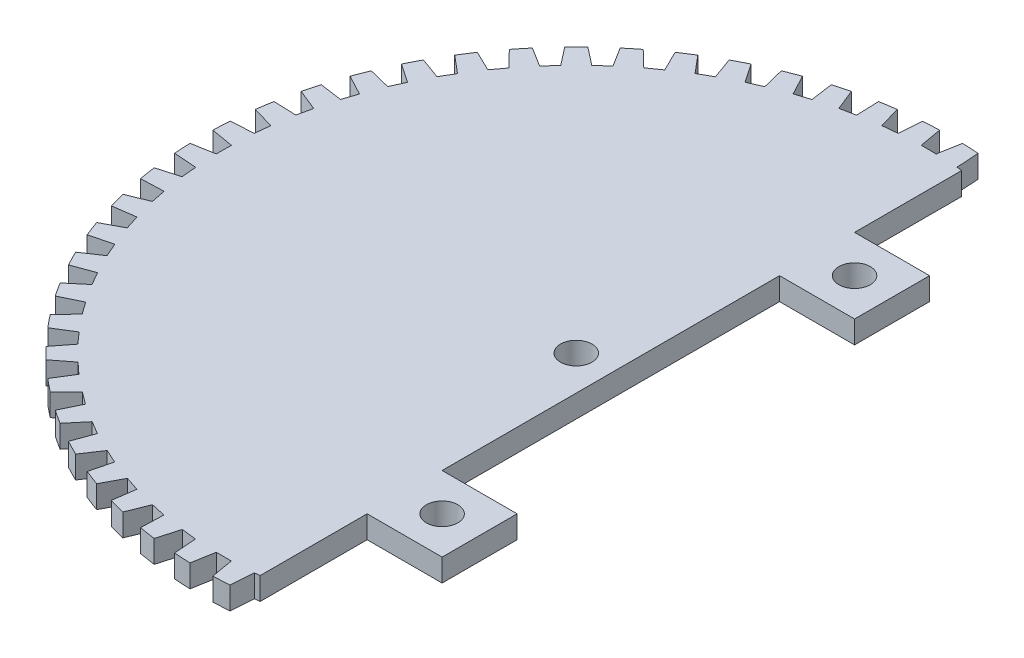
SolidWorks part; units mm, degrees
ref_plane "Спереди" through (0, 0, 0) normal (0, 0, 1) x (1, 0, 0)
ref_plane "Сверху" through (0, 0, 0) normal (0, 1, 0) x (1, 0, 0)
ref_plane "Справа" through (0, 0, 0) normal (1, 0, 0) x (0, 0, -1)
sketch "Эскиз1" plane through (0, 0, 0) normal (0, 1, 0) x (1, 0, 0)
  circle A0 centre (0, 0) radius 50
  dimension "D1" = 100
extrude "Бобышка-Вытянуть1" add sketch "Эскиз1" along normal blind 3
sketch "Эскиз2" plane through (0, 3, 0) normal (0, 1, 0) x (1, 0, 0)
  line L0 (0, 50) -> (0, 47)
  line L1 (-1, 47.0106) -> (1, 46.9894)
  line L2 (1, 46.9894) -> (1.5267, 49.9767)
  line L4 (-1, 47.0106) -> (-1.523, 49.9768)
  circle A0 centre (0, 0) radius 50 construction
  arc A1 (1, 46.9894) -> (0, 47) centre (0, 0) ccw
  arc A3 (1.5267, 49.9767) -> (-1.523, 49.9768) centre (0, 0) ccw
  point P11 (0, 47)
  dimension "D4" = 10
  dimension "D1" = 3
  dimension "D2" = 2
  dimension "D3" = 10
extrude "Вырез-Вытянуть1" cut sketch "Эскиз2" against normal blind 3 contours L1 L4 A3 L2
pattern_circular "Круговой массив1" count 60 over 360 about axis through (0, 0, 0) along (0, 1, 0) of "Вырез-Вытянуть1"
sketch "Эскиз3" plane through (0, 3, 0) normal (0, 1, 0) x (1, 0, 0)
  circle A0 centre (0, 0) radius 2.1
  dimension "D1" = 4.2
extrude "Вырез-Вытянуть2" cut sketch "Эскиз3" against normal blind 3
sketch "Эскиз6" plane through (0, 3, 0) normal (0, 1, 0) x (1, 0, 0)
  line L0 (4.6115, -19.6891) -> (4.6115, 19.6891) construction
  point P3 (4.6115, 0)
ref_plane "Плоскость1" through (4.6115, 0, 0) normal (1, 0, 0) x (0, 0, -1)
sketch "Эскиз7" plane through (4.6115, 0, 0) normal (1, 0, 0) x (0, 0, -1)
  line L1 (-53.0319, 13.837) -> (54.7228, 13.837)
  line L2 (-53.0319, 13.837) -> (-53.0319, -11.6798)
  line L3 (-53.0319, -11.6798) -> (54.7228, -11.6798)
  line L4 (54.7228, 13.837) -> (54.7228, -11.6798)
extrude "Вырез-Вытянуть3" cut sketch "Эскиз7" along normal blind 63
sketch "Эскиз8" plane through (0, 3, 0) normal (0, 1, 0) x (1, 0, 0)
  line L0 (4.6115, -46.771) -> (4.6115, 46.7774) construction
  line L1 (-5.3885, 32.5) -> (14.6115, 32.5)
  line L2 (-5.3885, 32.5) -> (-5.3885, 22.5)
  line L3 (-5.3885, 22.5) -> (14.6115, 22.5)
  line L4 (14.6115, 32.5) -> (14.6115, 22.5)
  line L5 (-5.3885, 32.5) -> (14.6115, 22.5) construction
  line L6 (-5.3885, 22.5) -> (14.6115, 32.5) construction
  line L8 (-5.3885, -22.5) -> (14.6115, -22.5)
  line L9 (-5.3885, -22.5) -> (-5.3885, -32.5)
  line L10 (-5.3885, -32.5) -> (14.6115, -32.5)
  line L11 (14.6115, -22.5) -> (14.6115, -32.5)
  line L12 (-5.3885, -22.5) -> (14.6115, -32.5) construction
  line L13 (-5.3885, -32.5) -> (14.6115, -22.5) construction
  point P0 (4.6115, 27.5)
  point P7 (4.6115, -27.5)
  dimension "D1" = 55
  dimension "D2" = 27.5
  dimension "D3" = 20
  dimension "D4" = 10
  dimension "D5" = 20
  dimension "D6" = 10
extrude "Бобышка-Вытянуть2" add sketch "Эскиз8" against normal up to surface (3 mm away) up to face at (0, 0, 2.1)
sketch "Эскиз9" plane through (0, 3, 0) normal (0, 1, 0) x (1, 0, 0)
  circle A0 centre (9.6115, 27.5) radius 2.1
  circle A1 centre (9.6115, -27.5) radius 2.1
  dimension "D1" = 4.2
  dimension "D2" = 4.2
extrude "Вырез-Вытянуть4" cut sketch "Эскиз9" against normal blind 19
